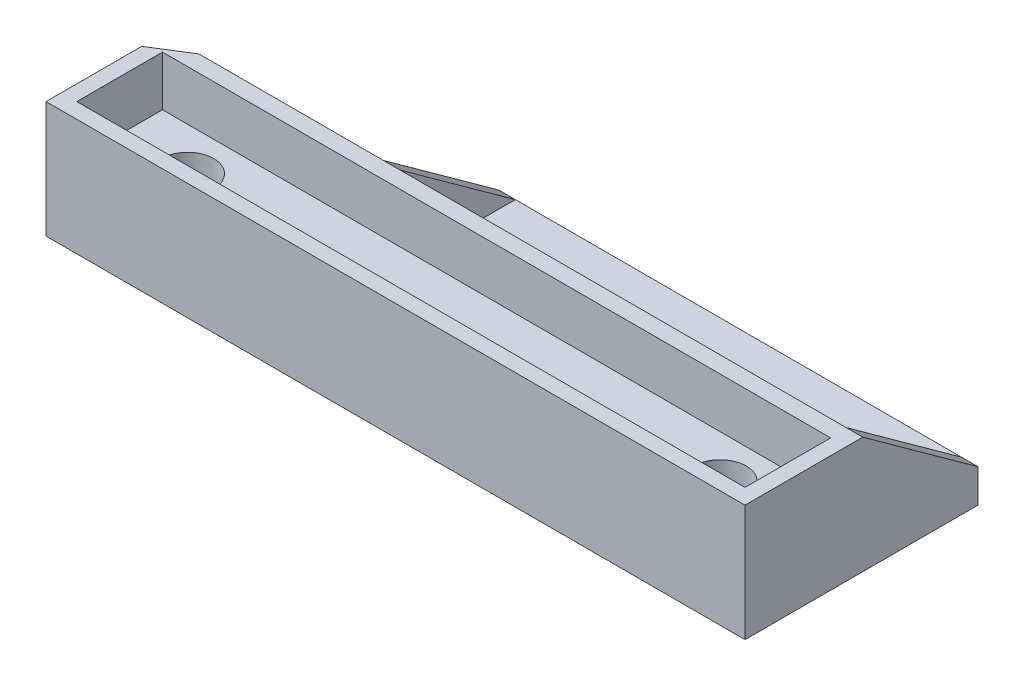
SolidWorks part; units mm, degrees
ref_plane "Front Plane" through (0, 0, 0) normal (0, 0, 1) x (1, 0, 0)
ref_plane "Top Plane" through (0, 0, 0) normal (0, 1, 0) x (1, 0, 0)
ref_plane "Right Plane" through (0, 0, 0) normal (1, 0, 0) x (0, 0, -1)
sketch "Sketch1" plane through (0, 0, 0) normal (0, 1, 0) x (1, 0, 0)
  line L1 (2.0004, 7) -> (42, 7)
  line L2 (0, 5.75) -> (0, 0)
  line L3 (0, 0) -> (42, 0)
  line L4 (42, 7) -> (42, 0)
  line L6 (0, 5.75) -> (2.0004, 7)
  dimension "D1" = 32
  dimension "D2" = 42
  dimension "D3" = 7
  dimension "D4" = 5.75
extrude "Riser" add sketch "Sketch1" along normal blind 7
sketch "Sketch2" plane through (0, 0, 0) normal (0, -1, 0) x (1, 0, 0)
  line L1 (21, 0) -> (21, -7) construction
  line L2 (0, 0) -> (42, 0) construction
  line L4 (42, -7) -> (2.0004, -7) construction
  line L5 (42, 0) -> (42, -7) construction
  circle A0 centre (37, -3.5) radius 1.575
  circle A2 centre (5, -3.5) radius 1.575
  point P6 (42, -3.5)
  dimension "D2" = 3.15
  dimension "D1" = 5
extrude "Mounting Holes" cut sketch "Sketch2" against normal through all
sketch "Sketch3" plane through (0, 7, 0) normal (0, 1, 0) x (1, 0, 0)
  line L5 (42, 7) -> (2.0004, 7) construction
  line L12 (0.925, 6.075) -> (41.075, 6.075)
  line L13 (0.925, 6.075) -> (0.925, 0.925)
  line L14 (0.925, 0.925) -> (41.075, 0.925)
  line L15 (41.075, 6.075) -> (41.075, 0.925)
  line L16 (42, 0) -> (42, 7) construction
  dimension "D1" = 5.15
  dimension "D2" = 40.15
  dimension "D3" = 0.925
  dimension "D4" = 0.925
extrude "Recess" cut sketch "Sketch3" against normal blind 3 contours L12 L15 L14 L13
sketch "Sketch4" plane through (0, 0, 0) normal (0, 1, 0) x (1, 0, 0)
  line L0 (-7.0926, 1.318) -> (28.8348, 23.768) construction
  line L1 (2.0004, 7) -> (42, 7)
  line L2 (42, 7) -> (42, 14)
  line L3 (42, 14) -> (13.2028, 14)
  line L4 (13.2028, 14) -> (2.0004, 7)
  dimension "D1" = 32
  dimension "D2" = 7
extrude "Flange" add sketch "Sketch4" along normal blind 7
sketch "Sketch5" plane through (0, 7, 0) normal (0, 1, 0) x (1, 0, 0)
  line L0 (14.2028, 7.075) -> (14.2028, 14)
  line L1 (42, 14) -> (13.2028, 14) construction
  line L2 (14.2028, 14) -> (41, 14)
  line L3 (41, 14) -> (41, 7.075)
  line L4 (41, 7.075) -> (14.2028, 7.075)
  line L5 (2.1204, 7.075) -> (13.2028, 7.075)
  line L6 (0.925, 6.075) -> (41.075, 6.075) construction
  line L7 (42, 0) -> (42, 14) construction
  line L8 (13.2028, 14) -> (0, 5.75) construction
  line L9 (13.2028, 7.075) -> (13.2028, 14)
  line L10 (13.2028, 14) -> (2.1204, 7.075)
  dimension "D2" = 1
  dimension "D3" = 1
  dimension "D4" = 1
extrude "Flange Cutout" cut sketch "Sketch5" against normal blind 5
sketch "Sketch7" plane through (41, 0, 0) normal (-1, 0, 0) x (0, 0, 1)
  line L0 (-7.075, 7) -> (-14, 2)
  line L1 (-14, 2) -> (-14, 7)
  line L2 (-14, 7) -> (-7.075, 7)
extrude "Angle Cutout" cut sketch "Sketch7" against normal through all and the other way through all
chamfer "Flange Chamfer 1" distance 1 angle 45 1 edges at (27.6014, 2, -7.075)
chamfer "Flange Chamfer 2" distance 1 angle 45 1 edges at (7.6616, 2, -7.075)
ref_plane "Mirror Plane" [suppressed] through (42, 0, 0) normal (1, 0, 0) x (0, 0, -1)
mirror "Mirror2" [suppressed] about plane through (42, 0, 0) normal (1, 0, 0)
delete or keep bodies "Body-Delete/Keep 1" [suppressed] type delete bodies bodies 112
